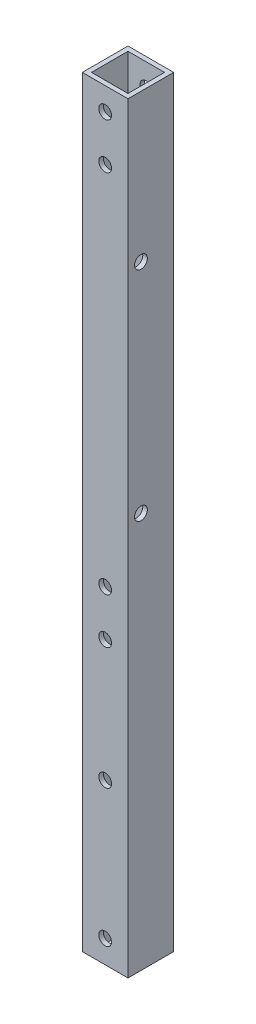
SolidWorks part; units mm, degrees
material "5052-H34"
ref_plane "正面" through (0, 0, 0) normal (0, 0, 1) x (1, 0, 0)
ref_plane "平面" through (0, 0, 0) normal (0, 1, 0) x (1, 0, 0)
ref_plane "右側面" through (0, 0, 0) normal (1, 0, 0) x (0, 0, -1)
sketch "ｽｹｯﾁ1" plane through (0, 0, 0) normal (0, 1, 0) x (1, 0, 0)
  line L1 (-7.5, 7.5) -> (7.5, 7.5)
  line L2 (-7.5, 7.5) -> (-7.5, -7.5)
  line L3 (-7.5, -7.5) -> (7.5, -7.5)
  line L4 (7.5, 7.5) -> (7.5, -7.5)
  line L5 (-7.5, 7.5) -> (7.5, -7.5) construction
  line L6 (-7.5, -7.5) -> (7.5, 7.5) construction
  point P0 (0, 0)
  dimension "D1" = 15
extrude "押し出し-薄板1" add sketch "ｽｹｯﾁ1" along normal blind 250 thin
sketch "ｽｹｯﾁ2" plane through (0, 0, 7.5) normal (0, 0, 1) x (1, 0, 0)
  line L0 (0, 0) -> (0, 52.5) construction
  circle A0 centre (0, 52.5) radius 2.1
  circle A1 centre (0, 7.5) radius 2.1
  circle A2 centre (0, 5) radius 2.1 construction
  dimension "D1" = 4.2
  dimension "D4" = 4.2
  dimension "D2" = 45
  dimension "D3" = 7.5
  dimension "D5" = 5
extrude "ｶｯﾄ - 押し出し1" cut sketch "ｽｹｯﾁ2" against normal through all
sketch "ｽｹｯﾁ3" plane through (0, 0, 7.5) normal (0, 0, 1) x (1, 0, 0)
  line L0 (0, 0) -> (0, 107.5) construction
  circle A0 centre (0, 107.5) radius 2.1
  circle A1 centre (0, 92.5) radius 2.1
  circle A2 centre (0, 52.5) radius 2.1 construction
  dimension "D1" = 4.2
  dimension "D2" = 40
  dimension "D3" = 15
extrude "ｶｯﾄ - 押し出し2" cut sketch "ｽｹｯﾁ3" against normal through all
sketch "ｽｹｯﾁ4" plane through (7.5, 0, 0) normal (1, 0, 0) x (0, 0, -1)
  line L0 (-3.25, 250) -> (-3.25, 0) construction
  line L1 (-7.5, 250) -> (7.5, 250) construction
  line L2 (-7.5, 0) -> (7.5, 0) construction
  line L3 (7.5, 250) -> (7.5, 0) construction
  circle A0 centre (-3.25, 130) radius 2.1
  circle A1 centre (-3.25, 201.5) radius 2.1
  dimension "D2" = 4.2
  dimension "D1" = 10.75
  dimension "D3" = 71.5
  dimension "D4" = 130
extrude "ｶｯﾄ - 押し出し3" cut sketch "ｽｹｯﾁ4" against normal through all
sketch "ｽｹｯﾁ5" plane through (0, 0, 7.5) normal (0, 0, 1) x (1, 0, 0)
  line L0 (0, 250) -> (0, 227.5) construction
  line L1 (-7.5, 250) -> (7.5, 250) construction
  circle A0 centre (0, 227.5) radius 2.1
  circle A1 centre (0, 242.5) radius 2.1
  dimension "D1" = 4.2
  dimension "D2" = 7.5
  dimension "D3" = 15
extrude "ｶｯﾄ - 押し出し4" cut sketch "ｽｹｯﾁ5" against normal through all
